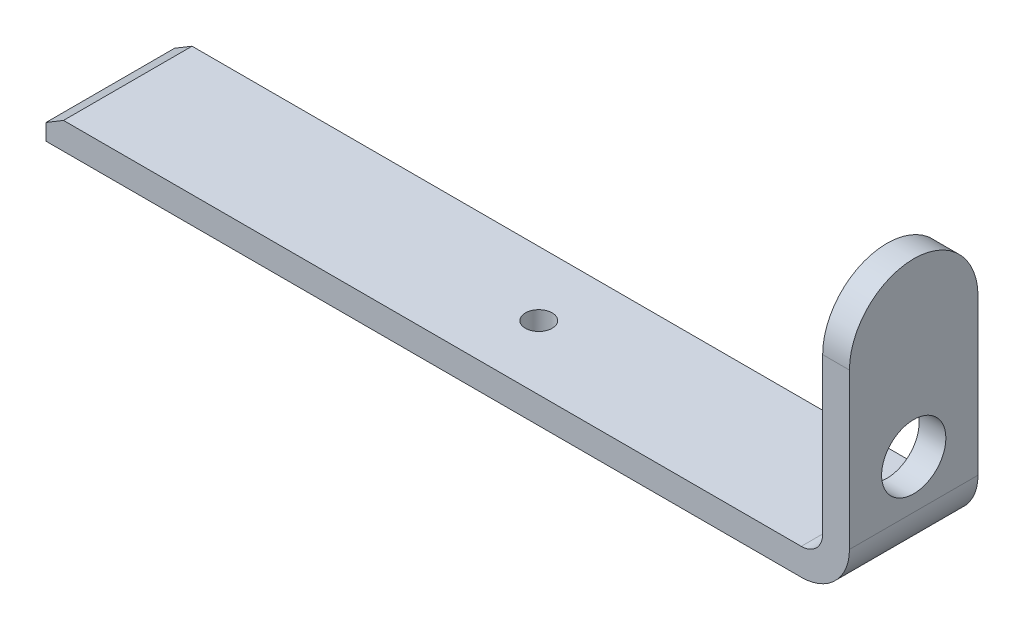
SolidWorks part; units mm, degrees
ref_plane "Front Plane" through (0, 0, 0) normal (0, 0, 1) x (1, 0, 0)
ref_plane "Top Plane" through (0, 0, 0) normal (0, 1, 0) x (1, 0, 0)
ref_plane "Right Plane" through (0, 0, 0) normal (1, 0, 0) x (0, 0, -1)
sketch "Sketch1" plane through (0, 0, 0) normal (1, 0, 0) x (0, 0, -1)
  line L2 (-10.8169, 22.0563) -> (-10.8169, -15.9437)
  line L3 (-10.8169, -15.9437) -> (13.1831, -15.9437)
  line L4 (13.1831, 22.0563) -> (13.1831, -15.9437)
  arc A0 (13.1831, 22.0563) -> (-10.8169, 22.0563) centre (1.1831, 22.0563) ccw
  circle A1 centre (1.1831, 2.0563) radius 6
  point P1 (1.1831, 0)
  dimension "D1" = 24
  dimension "D2" = 18
  dimension "D4" = 12
  dimension "36" = 38
  dimension "D3" = 12
extrude "Boss-Extrude1" add sketch "Sketch1" against normal blind 150
sketch "Sketch3" plane through (0, 0, -13.1831) normal (0, 0, -1) x (-1, 0, 0)
  line L0 (5, 34.0563) -> (5, -6.9437)
  line L1 (5, 34.0563) -> (150, 34.0563)
  line L2 (9, -10.9437) -> (150, -10.9437)
  line L3 (150, 34.0563) -> (150, -10.9437)
  line L4 (150, 34.0563) -> (0, 34.0563) construction
  line L5 (0, 34.0563) -> (0, 22.0563) construction
  line L6 (150, -15.9437) -> (0, -15.9437) construction
  line L7 (150, -15.9437) -> (150, 22.0563) construction
  arc A0 (9, -10.9437) -> (5, -6.9437) centre (9, -6.9437) cw
  dimension "D3" = 4
  dimension "D1" = 5
  dimension "D2" = 5
extrude "Cut-Extrude1" cut sketch "Sketch3" against normal blind 150
sketch "Sketch4" plane through (0, 0, -13.1831) normal (0, 0, -1) x (-1, 0, 0)
  line L0 (146.7318, -10.9437) -> (150, -12.9101)
  line L1 (9, -10.9437) -> (150, -10.9437) construction
  line L2 (150, -15.9437) -> (150, -10.9437) construction
  line L3 (150, -12.9101) -> (150, -10.9437)
  line L4 (150, -10.9437) -> (146.7318, -10.9437)
  line L5 (150, -15.9437) -> (0, -15.9437) construction
  line L6 (0, -15.9437) -> (0, 22.0563) construction
  line L7 (0, -6.9437) -> (0, -15.9437)
  line L8 (0, -15.9437) -> (8.9997, -15.9437)
  arc A0 (8.9997, -15.9437) -> (0, -6.9437) centre (9, -6.9437) cw
  dimension "D1" = 3.2682
extrude "Cut-Extrude2" cut sketch "Sketch4" against normal blind 150
sketch "Sketch6" plane through (0, -10.9437, 0) normal (0, 1, 0) x (1, 0, 0)
  line L0 (-150, -10.8169) -> (-150, 13.1831) construction
  line L1 (-146.7318, -10.8169) -> (-9, -10.8169) construction
  circle A0 centre (-70, 1.1831) radius 2.5
  dimension "D1" = 80
  dimension "D2" = 5
  dimension "D3" = 12
extrude "Cut-Extrude3" cut sketch "Sketch6" against normal blind 150
